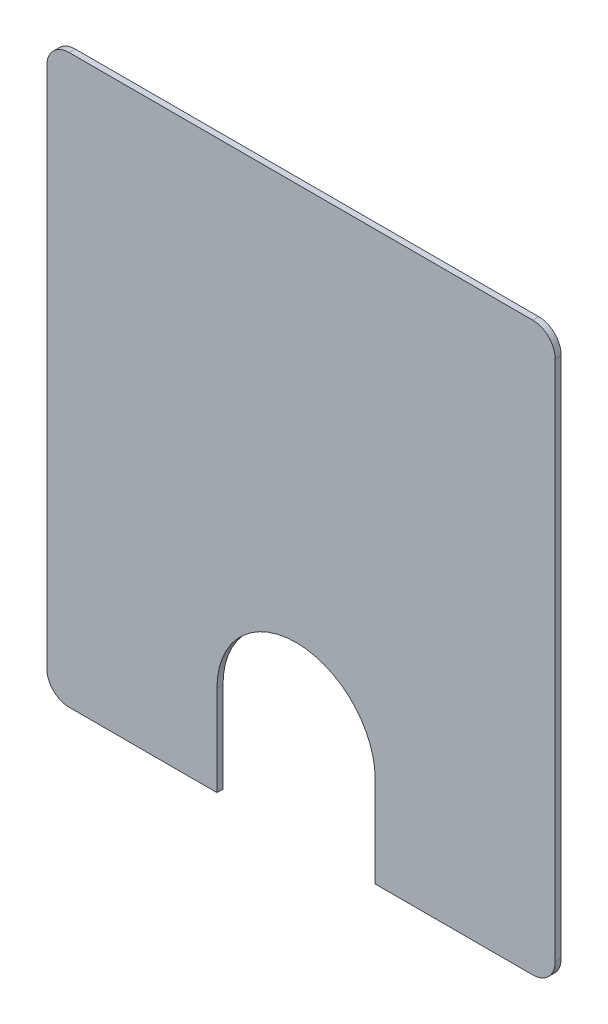
SolidWorks part; units mm, degrees
ref_plane "Front Plane" through (0, 0, 0) normal (0, 0, 1) x (1, 0, 0)
ref_plane "Top Plane" through (0, 0, 0) normal (0, 1, 0) x (1, 0, 0)
ref_plane "Right Plane" through (0, 0, 0) normal (1, 0, 0) x (0, 0, -1)
sketch "Sketch1" plane through (0, 0, 0) normal (0, 0, 1) x (1, 0, 0)
  line L0 (0, -126.6) -> (0, -123.7195) construction
  line L1 (-103.5, 126.6) -> (103.5, 126.6)
  line L2 (-113.5, 116.6) -> (-113.5, -116.6)
  line L3 (-103.5, -126.6) -> (-37.5249, -126.6)
  line L4 (113.5, 116.6) -> (113.5, -116.6)
  line L5 (-113.5, 126.6) -> (113.5, -126.6) construction
  line L6 (-113.5, -126.6) -> (113.5, 126.6) construction
  line L7 (33.1499, -86.2035) -> (33.1499, -126.6)
  line L8 (-37.5249, -86.2035) -> (-37.5249, -126.6)
  line L9 (33.1499, -126.6) -> (103.5, -126.6)
  arc A0 (-113.5, -116.6) -> (-103.5, -126.6) centre (-103.5, -116.6) ccw
  arc A1 (103.5, -126.6) -> (113.5, -116.6) centre (103.5, -116.6) ccw
  arc A2 (103.5, 126.6) -> (113.5, 116.6) centre (103.5, 116.6) cw
  arc A3 (-103.5, 126.6) -> (-113.5, 116.6) centre (-103.5, 116.6) ccw
  arc A4 (33.1499, -86.2035) -> (-37.5249, -86.2035) centre (-2.1875, -86.2035) ccw
  point P0 (0, 0)
  dimension "D3" = 10
  dimension "D4" = 35.3374
  dimension "D1" = 253.2
  dimension "D2" = 227
  dimension "D5" = 40.3965
extrude "Boss-Extrude1" add sketch "Sketch1" along normal blind 2.7
